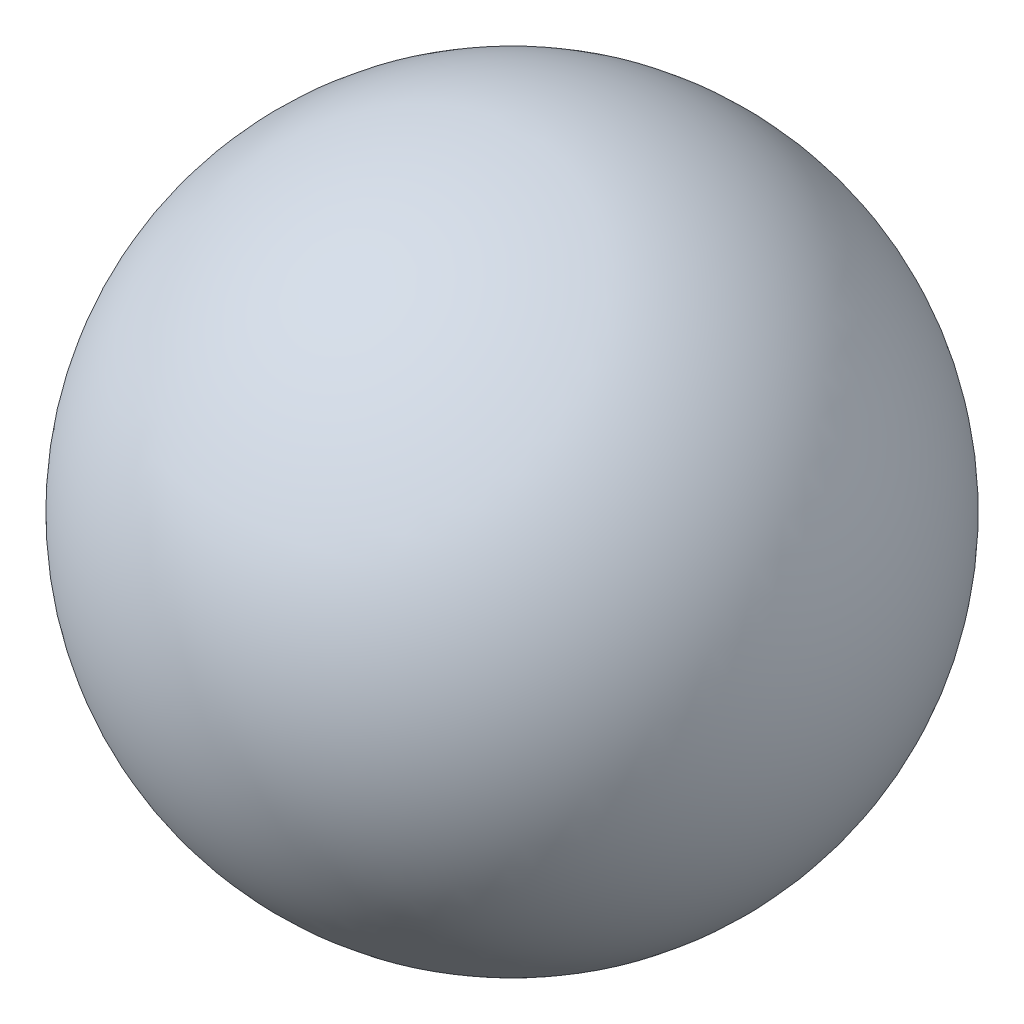
SolidWorks part; units mm, degrees
ref_plane "Front Plane" through (0, 0, 0) normal (0, 0, 1) x (1, 0, 0)
ref_plane "Top Plane" through (0, 0, 0) normal (0, 1, 0) x (1, 0, 0)
ref_plane "Right Plane" through (0, 0, 0) normal (1, 0, 0) x (0, 0, -1)
sketch "Sketch1" plane through (0, 0, 0) normal (0, 0, 1) x (1, 0, 0)
  line L0 (0, 63.5) -> (0, -63.5)
  arc A0 (0, 63.5) -> (0, -63.5) centre (0, 0) cw
  dimension "D1" = 127
revolve "Revolve1" add sketch "Sketch1" angle 360 about L0
sketch3d "3DSketch1"
  point P0 (0, 0, 0)
